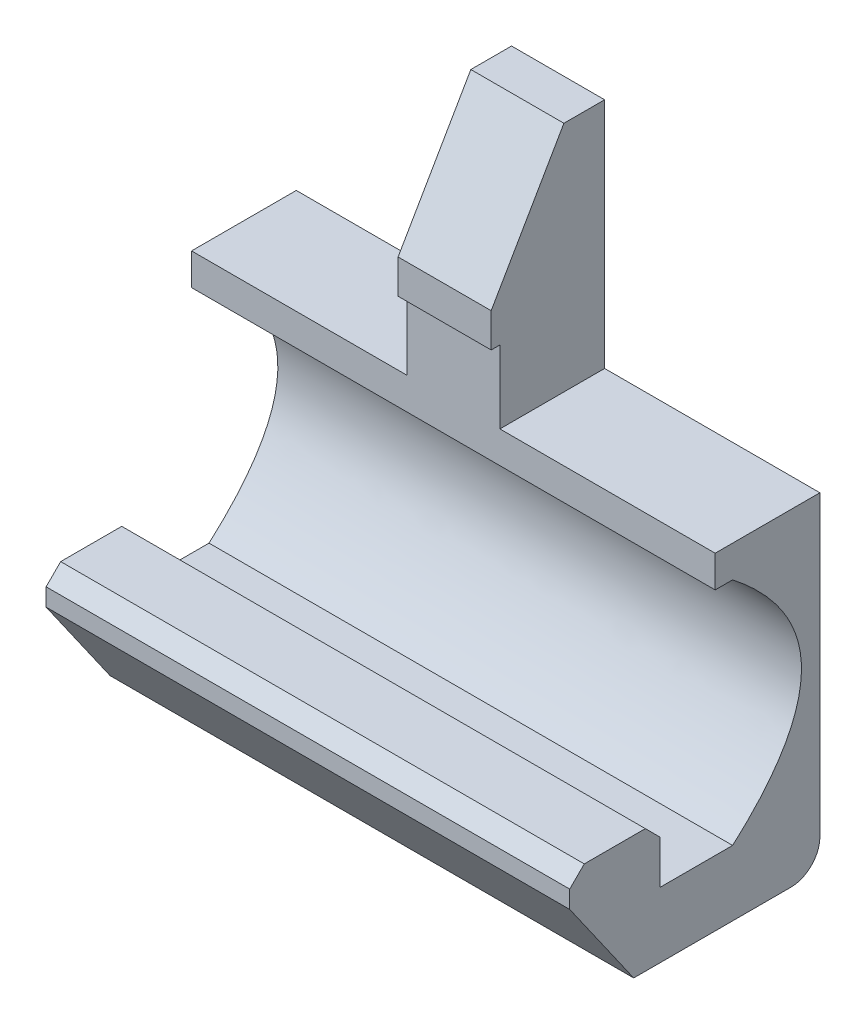
SolidWorks part; units mm, degrees
ref_plane "Front Plane" through (0, 0, 0) normal (0, 0, 1) x (1, 0, 0)
ref_plane "Top Plane" through (0, 0, 0) normal (0, 1, 0) x (1, 0, 0)
ref_plane "Right Plane" through (0, 0, 0) normal (1, 0, 0) x (0, 0, -1)
sketch "Sketch1" plane through (0, 0, 0) normal (0, 1, 0) x (1, 0, 0)
  line L1 (-2.5, 2.5) -> (2.5, 2.5)
  line L2 (-2.5, 2.5) -> (-2.5, -2.5)
  line L3 (-2.5, -2.5) -> (2.5, -2.5)
  line L4 (2.5, 2.5) -> (2.5, -2.5)
  line L5 (-2.5, 2.5) -> (2.5, -2.5) construction
  line L6 (-2.5, -2.5) -> (2.5, 2.5) construction
  point P0 (0, 0)
  dimension "D1" = 5
extrude "Boss-Extrude1" add sketch "Sketch1" along normal blind 2
sketch "Sketch2" plane through (0, 2, 0) normal (0, 1, 0) x (1, 0, 0)
  line L0 (2.5, 2.5) -> (-2.5, 2.5) construction
  line L1 (-1.6, 2.5) -> (1.6, 2.5)
  line L2 (-1.6, 2.5) -> (-1.6, -0.5)
  line L3 (-1.6, -0.5) -> (1.6, -0.5)
  line L4 (1.6, 2.5) -> (1.6, -0.5)
  point P6 (0, 2.5)
  dimension "D1" = 3.2
  dimension "D2" = 3
extrude "Boss-Extrude2" add sketch "Sketch2" along normal blind 5
sketch "Sketch3" plane through (0, 7, 0) normal (0, 1, 0) x (1, 0, 0)
  line L0 (1.6, -0.5) -> (1.6, 2.5) construction
  line L1 (-1.6, 2.5) -> (1.6, 2.5)
  line L2 (-1.6, 2.5) -> (-1.6, -1.1)
  line L3 (-1.6, -1.1) -> (1.6, -1.1)
  line L4 (1.6, 2.5) -> (1.6, -1.1)
  dimension "D1" = 3.6
extrude "Boss-Extrude3" add sketch "Sketch3" along normal blind 3
sketch "Sketch4" plane through (1.6, 0, 0) normal (1, 0, 0) x (0, 0, -1)
  line L0 (-1.1, 7) -> (0.75, 10)
  line L1 (0.75, 10) -> (-1.1, 10)
  line L2 (-1.1, 10) -> (-1.1, 7)
  point P4 (0.8217, 10)
  dimension "D1" = 1.75
extrude "Cut-Extrude1" cut sketch "Sketch4" against normal through all
sketch "Sketch6" plane through (0, 0, 2.5) normal (0, 0, 1) x (1, 0, 0)
  line L4 (-2.5, 0) -> (2.5, 0)
  line L5 (2.5, 0) -> (2.5, 2)
  line L6 (2.5, 2) -> (-2.5, 2)
  line L7 (-2.5, 2) -> (-2.5, 0)
  line L8 (-2.5, 0) -> (2.5, 0)
  line L9 (2.5, 0) -> (2.5, 2)
  line L10 (2.5, 2) -> (-2.5, 2)
  line L11 (-2.5, 2) -> (-2.5, 0)
  dimension "D1" = 0
extrude "Cut-Extrude2" cut sketch "Sketch6" against normal through all
sketch "Sketch7" plane through (0, 2, 0) normal (0, -1, 0) x (1, 0, 0)
  line L0 (1.6, -2.5) -> (-1.6, -2.5) construction
  line L1 (-9, -2.5) -> (9, -2.5)
  line L2 (-9, -2.5) -> (-9, 1.5)
  line L3 (-9, 1.5) -> (9, 1.5)
  line L4 (9, -2.5) -> (9, 1.5)
  point P6 (0, 1.5)
  dimension "D1" = 18
  dimension "D2" = 4
extrude "Boss-Extrude5" add sketch "Sketch7" along normal blind 13
sketch "Sketch8" plane through (0, 0, 1.5) normal (0, 0, 1) x (1, 0, 0)
  line L0 (9, -11) -> (9, 2) construction
  line L1 (-9, -11) -> (9, -11)
  line L2 (-9, -11) -> (-9, -5)
  line L3 (-9, -5) -> (9, -5)
  line L4 (9, -11) -> (9, -5)
  dimension "D1" = 6
extrude "Boss-Extrude6" add sketch "Sketch8" along normal blind 4
sketch "Sketch9" plane through (9, 0, 0) normal (1, 0, 0) x (0, 0, -1)
  line L1 (-3, -5) -> (-1.5, -5)
  line L2 (-3, -5) -> (-3, -7)
  line L3 (-3, -7) -> (-1.5, -7)
  line L4 (-1.5, -5) -> (-1.5, -7)
  line L5 (-1.5, -5) -> (-1.5, 2) construction
  line L6 (-5.5, -5) -> (-1.5, -5) construction
  point P4 (-3, -7.3249)
  dimension "D1" = 1.5
  dimension "D2" = 2
extrude "Cut-Extrude4" cut sketch "Sketch9" against normal through all
sketch "Sketch10" plane through (9, 0, 0) normal (1, 0, 0) x (0, 0, -1)
  line L0 (-0.5, 7) -> (-0.5, 2) construction
  line L1 (-1.5, 2) -> (-0.5, 2)
  line L2 (-1.5, 2) -> (-1.5, -7)
  line L3 (-1.5, -7) -> (-0.5, -7)
  line L4 (-0.5, 2) -> (-0.5, -7)
  line L5 (-3, -7) -> (-1.5, -7) construction
extrude "Cut-Extrude5" cut sketch "Sketch10" against normal through all
sketch "Sketch11" plane through (9, 0, 0) normal (1, 0, 0) x (0, 0, -1)
  line L0 (-0.5, -7) -> (-0.5, 2) construction
  line L1 (-0.5, 0.9064) -> (-0.5, -7)
  line L2 (2.5, -11) -> (2.5, 2) construction
  spline S0 degree 2 poles (-0.5, 0.9064) (4.233, -2.8097) (-0.5, -7) knots 0 0 0 1 1 1
  point P2 (1.9949, -2.599)
  dimension "D1" = 0.65
extrude "Cut-Extrude6" cut sketch "Sketch11" against normal through all
sketch "Sketch12" plane through (0, 0, 0.5) normal (0, 0, 1) x (1, 0, 0)
  line L16 (-9, 2) -> (-9, 0.9064)
  line L17 (-9, 2) -> (-9, 0.9064)
  line L18 (-9, 0.9064) -> (9, 0.9064)
  line L19 (9, 2) -> (1.6, 2)
  line L20 (1.6, 2) -> (1.6, 7)
  line L21 (1.6, 7) -> (-1.6, 7)
  line L22 (-1.6, 7) -> (-1.6, 2)
  line L23 (-9, 0.9064) -> (9, 0.9064)
  line L27 (9, 2) -> (1.6, 2)
  line L28 (1.6, 2) -> (1.6, 7)
  line L29 (1.6, 7) -> (-1.6, 7)
  line L30 (-1.6, 7) -> (-1.6, 2)
  line L32 (9, 0.9064) -> (9, 2)
  line L33 (9, 0.9064) -> (9, 2)
  line L34 (-1.6, 2) -> (-9, 2)
  line L35 (-1.6, 2) -> (-9, 2)
  dimension "D1" = 0
extrude "Boss-Extrude7" add sketch "Sketch12" along normal blind 0.6
sketch "Sketch13" plane through (-1.6, 0, 0) normal (-1, 0, 0) x (0, 0, 1)
  line L0 (1.1, 7) -> (1.1, 2) construction
  line L1 (1.4, 4.5) -> (-2.5, 4.5)
  line L2 (1.4, 4.5) -> (1.4, 10)
  line L3 (1.4, 10) -> (-2.5, 10)
  line L4 (-2.5, 4.5) -> (-2.5, 10)
  line L5 (-2.5, 2) -> (1.1, 2) construction
  dimension "D1" = 0.3
  dimension "D2" = 2.5
extrude "Boss-Extrude8" add sketch "Sketch13" against normal up to surface (3.2 mm away) up to face at (1.6, 6.2, -0.71)
chamfer "Chamfer2" distance 2.5 angle 60 1 edges at (0, 10, 1.4)
sketch "Sketch14" plane through (9, 0, 0) normal (1, 0, 0) x (0, 0, -1)
  line L0 (2.5, -11) -> (2.5, 2) construction
  line L1 (-5.5, -11) -> (2.5, -11)
  line L2 (-5.5, -11) -> (-5.5, -9.247)
  line L3 (-5.5, -9.247) -> (2.5, -9.247)
  line L4 (2.5, -11) -> (2.5, -9.247)
  dimension "D1" = 1.753
extrude "Cut-Extrude7" cut sketch "Sketch14" against normal through all
sketch "Sketch16" plane through (0, 0, 5.5) normal (0, 0, 1) x (1, 0, 0)
  line L4 (-9, -5) -> (-9, -9.247)
  line L5 (-9, -9.247) -> (9, -9.247)
  line L6 (9, -9.247) -> (9, -5)
  line L7 (9, -5) -> (-9, -5)
  line L8 (-9, -5) -> (-9, -9.247)
  line L9 (-9, -9.247) -> (9, -9.247)
  line L10 (9, -9.247) -> (9, -5)
  line L11 (9, -5) -> (-9, -5)
  dimension "D1" = 0
extrude "Boss-Extrude9" add sketch "Sketch16" along normal blind 0.6
chamfer "Chamfer4" distance 2.2 angle 55 1 edges at (0, -9.247, 6.1)
chamfer "Chamfer5" distance 0.5 angle 45 2 edges at (0, -5, 3) (0, -5, 6.1)
fillet "Fillet1" radius 1 1 edges at (0, -9.247, -2.5)
